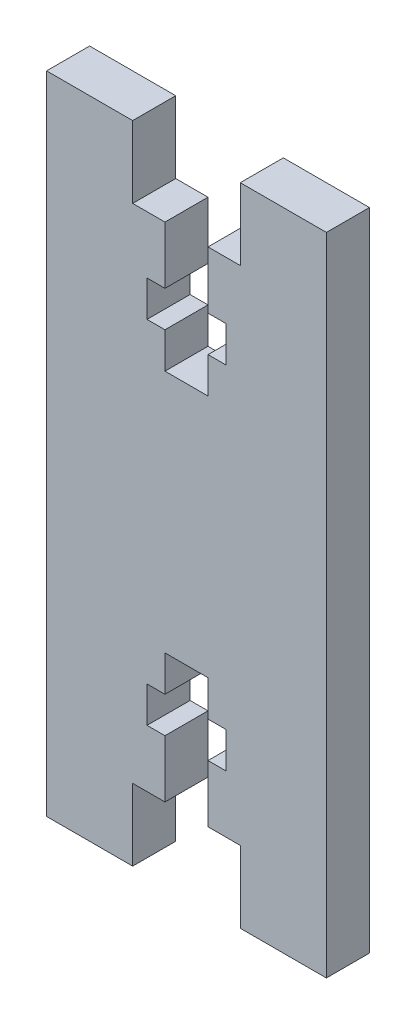
SolidWorks part; units mm, degrees
material "Pinho"
ref_plane "Plano frontal" through (0, 0, 0) normal (0, 0, 1) x (1, 0, 0)
ref_plane "Plano superior" through (0, 0, 0) normal (0, 1, 0) x (1, 0, 0)
ref_plane "Plano direito" through (0, 0, 0) normal (1, 0, 0) x (0, 0, -1)
sketch "Esboço1" plane through (0, 0, 0) normal (0, 0, 1) x (1, 0, 0)
  line L0 (0, 0) -> (2.25, 0)
  line L1 (7.5, 0) -> (7.5, 5)
  line L2 (7.5, 5) -> (13.5, 5)
  line L3 (13.5, 5) -> (13.5, 0)
  line L4 (0, 0) -> (0, 5)
  line L5 (0, 5) -> (-6, 5)
  line L6 (-6, 5) -> (-6, 0)
  line L7 (2.25, -4) -> (2.25, 0)
  line L8 (1, -4) -> (2.25, -4)
  line L9 (-6, -40) -> (-6, -35)
  line L10 (0, -40) -> (-6, -40)
  line L11 (0, -35) -> (0, -40)
  line L12 (13.5, -40) -> (13.5, -35)
  line L13 (7.5, -40) -> (13.5, -40)
  line L14 (7.5, -35) -> (7.5, -40)
  line L15 (0, -35) -> (2.25, -35)
  line L16 (-6, 0) -> (-6, -35)
  line L17 (13.5, 0) -> (13.5, -35)
  line L18 (5.25, -4) -> (5.25, 0)
  line L19 (6.5, -4) -> (5.25, -4)
  line L20 (6.5, -6.5) -> (6.5, -4)
  line L21 (5.25, -6.5) -> (6.5, -6.5)
  line L22 (5.25, -9) -> (5.25, -6.5)
  line L23 (2.25, -6.5) -> (2.25, -9)
  line L24 (2.25, -9) -> (5.25, -9)
  line L25 (1, -6.5) -> (2.25, -6.5)
  line L26 (1, -4) -> (1, -6.5)
  line L27 (5.25, -35) -> (7.5, -35)
  line L28 (5.25, -31) -> (5.25, -35)
  line L29 (6.5, -31) -> (5.25, -31)
  line L30 (2.25, -31) -> (2.25, -35)
  line L31 (1, -31) -> (2.25, -31)
  line L32 (1, -28.5) -> (1, -31)
  line L33 (2.25, -28.5) -> (1, -28.5)
  line L34 (2.25, -26) -> (2.25, -28.5)
  line L35 (5.25, -28.5) -> (5.25, -26)
  line L36 (5.25, -26) -> (2.25, -26)
  line L37 (6.5, -28.5) -> (5.25, -28.5)
  line L38 (6.5, -31) -> (6.5, -28.5)
  line L40 (5.25, 0) -> (7.5, 0)
extrude "Ressalto-extrusão1" add sketch "Esboço1" along normal blind 3
